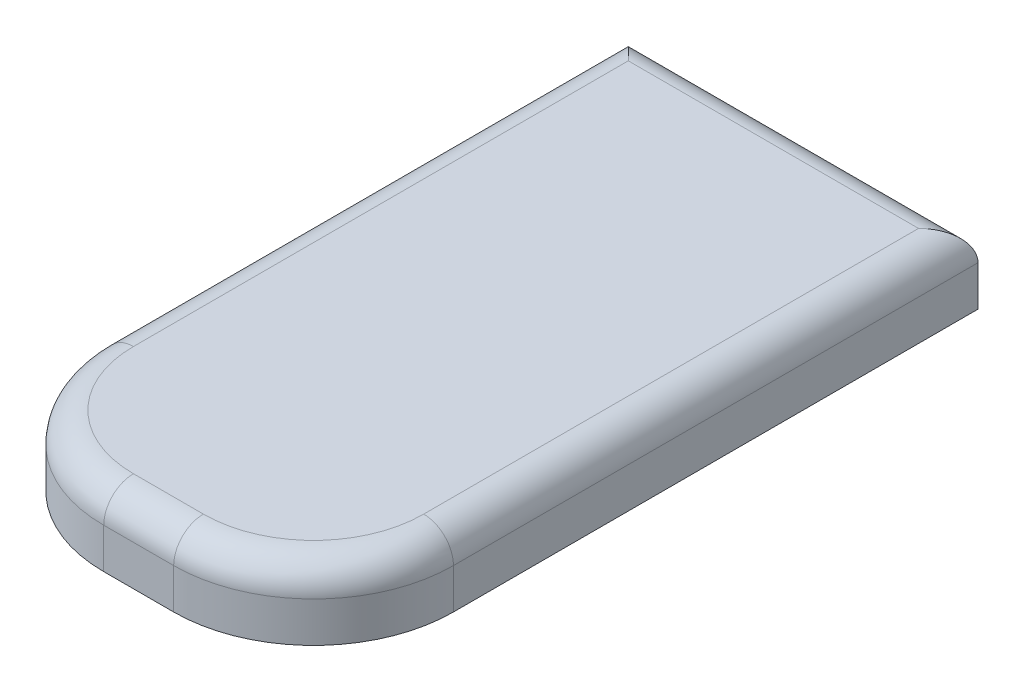
SolidWorks part; units mm, degrees
ref_plane "Front Plane" through (0, 0, 0) normal (0, 0, 1) x (1, 0, 0)
ref_plane "Top Plane" through (0, 0, 0) normal (0, 1, 0) x (1, 0, 0)
ref_plane "Right Plane" through (0, 0, 0) normal (1, 0, 0) x (0, 0, -1)
sketch "Sketch2" plane through (0, 0, 0) normal (0, 0, 1) x (1, 0, 0)
  line L1 (0, 101.6) -> (508, 101.6)
  line L2 (0, 101.6) -> (0, 0)
  line L3 (0, 0) -> (508, 0)
  line L4 (508, 101.6) -> (508, 0)
  dimension "D1" = 101.6
  dimension "D2" = 508
extrude "Boss-Extrude2" add sketch "Sketch2" along normal blind 965.2 contours L2 L1 L4 L3
sketch "Sketch3" plane through (0, 0, 0) normal (0, -1, 0) x (-1, 0, 0)
  line L17 (-406.4, -215.9) -> (-381, -215.9)
  line L18 (-406.4, -215.9) -> (-406.4, -241.3)
  line L19 (-406.4, -241.3) -> (-381, -241.3)
  line L20 (-381, -215.9) -> (-381, -241.3)
  line L21 (-406.4, -215.9) -> (-381, -241.3) construction
  line L22 (-406.4, -241.3) -> (-381, -215.9) construction
  line L27 (-127, -215.9) -> (-101.6, -215.9)
  line L28 (-127, -215.9) -> (-127, -241.3)
  line L29 (-127, -241.3) -> (-101.6, -241.3)
  line L30 (-101.6, -215.9) -> (-101.6, -241.3)
  line L31 (-127, -215.9) -> (-101.6, -241.3) construction
  line L32 (-127, -241.3) -> (-101.6, -215.9) construction
  circle A0 centre (-88.9, -736.6) radius 25.4
  circle A1 centre (-419.1, -736.6) radius 25.4
extrude "Cut-Extrude1" cut sketch "Sketch3" against normal blind 50.8
fillet "Fillet1" radius 203.2 1 edges at (0, 50.8, 965.2)
fillet "Fillet2" radius 203.2 1 edges at (508, 50.8, 965.2)
fillet "Fillet4" radius 43.18 6 edges at (508, 101.6, 381) (254, 101.6, 0) (0, 101.6, 381) (59.5159, 101.6, 905.6841) (254, 101.6, 965.2) (448.4841, 101.6, 905.6841)
